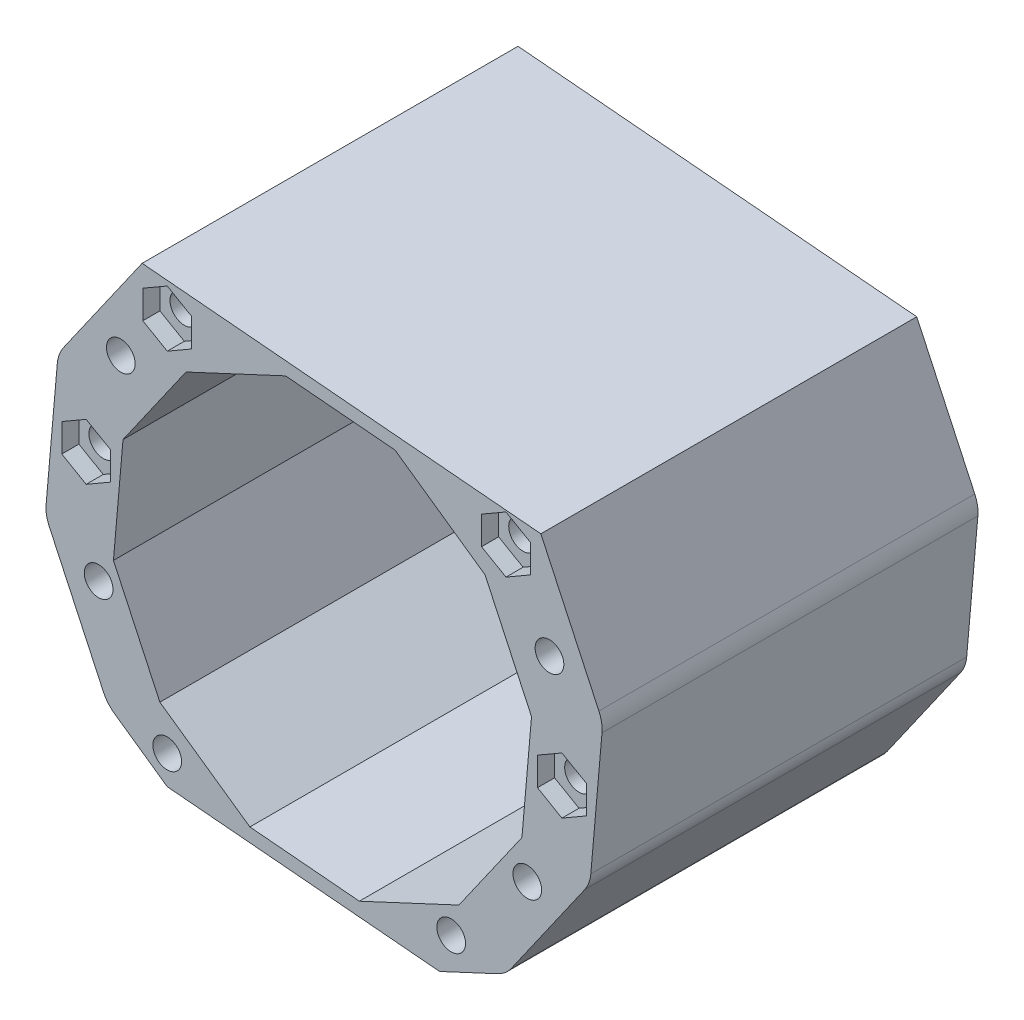
SolidWorks part; units mm, degrees
material "PE faible/moyenne densité"
ref_plane "Plan de face" through (0, 0, 0) normal (0, 0, 1) x (1, 0, 0)
ref_plane "Plan de dessus" through (0, 0, 0) normal (0, 1, 0) x (1, 0, 0)
ref_plane "Plan de droite" through (0, 0, 0) normal (1, 0, 0) x (0, 0, -1)
sketch "Esquisse1" plane through (0, 0, 0) normal (0, 0, 1) x (1, 0, 0)
  line L0 (16.9047, -36.2523) -> (26.6185, -31.7227)
  line L2 (-26.6185, 31.7227) -> (-38.9137, 14.1634)
  line L3 (-38.9137, 14.1634) -> (-40.7819, -7.191)
  line L4 (-40.7819, -7.191) -> (-31.7227, -26.6185)
  line L5 (-31.7227, -26.6185) -> (-22.9431, -32.7661)
  line L7 (26.6185, -31.7227) -> (38.9137, -14.1634)
  line L8 (38.9137, -14.1634) -> (40.7819, 7.191)
  line L9 (40.7819, 7.191) -> (31.7227, 26.6185)
  line L12 (-26.6185, 31.7227) -> (31.7227, 26.6185)
  line L13 (16.9047, -36.2523) -> (-22.9431, -32.7661)
  line L15 (-7.191, 40.7819) -> (-26.6185, 31.7227) [skipped]
  line L16 (14.1634, 38.9137) -> (-7.191, 40.7819) [skipped]
  line L17 (31.7227, 26.6185) -> (14.1634, 38.9137) [skipped]
  line L18 (-14.1634, -38.9137) -> (7.191, -40.7819) [skipped]
  arc A0 (-26.6185, 31.7227) -> (-31.7227, -26.6185) centre (0, 0) ccw construction
  arc A1 (26.6185, -31.7227) -> (31.7227, 26.6185) centre (0, 0) ccw construction
  dimension "D1" = 80
extrude "Boss.-Extru.1" add sketch "Esquisse1" along normal blind 10
sketch "Esquisse2" plane through (0, 0, 10) normal (0, 0, 1) x (1, 0, 0)
  line L0 (38.9137, -14.1634) -> (40.7819, 7.191) construction
  line L1 (-20.1941, 21.1611) -> (-29.4154, 7.9916)
  line L2 (-29.4154, 7.9916) -> (-30.8166, -8.0242)
  line L3 (-30.8166, -8.0242) -> (-24.0222, -22.5948)
  line L4 (-24.0222, -22.5948) -> (-10.8527, -31.8162)
  line L5 (-10.8527, -31.8162) -> (5.163, -33.2174)
  line L6 (5.163, -33.2174) -> (19.7337, -26.423)
  line L7 (19.7337, -26.423) -> (28.9551, -13.2535)
  line L8 (28.9551, -13.2535) -> (30.3563, 2.7622)
  line L9 (30.3563, 2.7622) -> (23.5618, 17.3329)
  line L10 (23.5618, 17.3329) -> (10.3924, 26.5543)
  line L11 (10.3924, 26.5543) -> (-5.6234, 27.9555)
  line L12 (-5.6234, 27.9555) -> (-20.1941, 21.1611)
  line L13 (-22.9431, -32.7661) -> (16.9047, -36.2523) construction
  line L14 (31.7227, 26.6185) -> (-26.6185, 31.7227)
  line L15 (-26.6185, 31.7227) -> (-38.9137, 14.1634)
  line L16 (-38.9137, 14.1634) -> (-40.7819, -7.191)
  line L17 (-40.7819, -7.191) -> (-31.7227, -26.6185)
  line L18 (-31.7227, -26.6185) -> (-22.9431, -32.7661)
  line L19 (-22.9431, -32.7661) -> (16.9047, -36.2523)
  line L20 (16.9047, -36.2523) -> (26.6185, -31.7227)
  line L21 (26.6185, -31.7227) -> (38.9137, -14.1634)
  line L22 (38.9137, -14.1634) -> (40.7819, 7.191)
  line L23 (40.7819, 7.191) -> (31.7227, 26.6185)
  circle A0 centre (-0.2302, -2.631) radius 30 construction
  circle A1 centre (34.8067, -3.7381) radius 2.1
  circle A2 centre (29.7378, -18.4699) radius 2.1
  circle A7 centre (-32.9816, -11.7341) radius 2.1
  circle A8 centre (-34.8067, 3.7381) radius 2.1
  circle A9 centre (-29.7378, 18.4699) radius 2.1
  circle A14 centre (32.9816, 11.7341) radius 2.1
  arc A15 (4.8041, -32.787) -> (2.9306, -33.0221) centre (4.1008, -34.7658) ccw [skipped]
  circle A16 centre (18.6013, -30.822) radius 2.1
  arc A17 (-13.4301, -33.5984) -> (-9.4662, -33.9452) centre (-11.3896, -33.1022) ccw [skipped]
  circle A18 centre (-24.6241, -24.8823) radius 2.1 [skipped]
  circle A19 centre (18.779, -29.5436) radius 2.1 [skipped]
  circle A20 centre (11.3896, 33.1022) radius 2.1 [skipped]
  circle A21 centre (-4.1008, 34.7658) radius 2.1 [skipped]
  circle A22 centre (24.6241, 24.8823) radius 2.1 [skipped]
  arc A23 (-17.1728, 30.8963) -> (-20.126, 31.1547) centre (-18.779, 29.5436) ccw [skipped]
  circle A24 centre (-22.9431, -28.5378) radius 2.1
  circle A25 centre (26.6185, 22.7059) radius 2.1
  circle A26 centre (-22.9431, 26.5543) radius 2.1
  point P68 (0, 0)
  dimension "D3" = 4.2
  dimension "D6" = 4.2
  dimension "D7" = 4.2
  dimension "D8" = 4.2
  dimension "D9" = 4.2
  dimension "D1" = 60
  dimension "D2" = 2
  dimension "D4" = 5
  dimension "D5" = 14
extrude "Boss.-Extru.2" add sketch "Esquisse2" along normal blind 45
sketch "Esquisse3" plane through (0, 0, 55) normal (0, 0, 1) x (1, 0, 0)
  line L1 (-34.8067, -0.3784) -> (-31.2417, 1.6798)
  line L2 (-31.2417, 1.6798) -> (-31.2417, 5.7963)
  line L3 (-31.2417, 5.7963) -> (-34.8067, 7.8546)
  line L4 (-34.8067, 7.8546) -> (-38.3717, 5.7963)
  line L5 (-38.3717, 5.7963) -> (-38.3717, 1.6798)
  line L6 (-38.3717, 1.6798) -> (-34.8067, -0.3784)
  line L7 (-22.9431, 22.4262) -> (-19.3681, 24.4902)
  line L8 (-19.3681, 24.4902) -> (-19.3681, 28.6183)
  line L9 (-19.3681, 28.6183) -> (-22.9431, 30.6823)
  line L10 (-22.9431, 30.6823) -> (-26.5181, 28.6183)
  line L11 (-26.5181, 28.6183) -> (-26.5181, 24.4902)
  line L12 (-26.5181, 24.4902) -> (-22.9431, 22.4262)
  line L13 (30.1935, 20.6418) -> (30.1935, 24.7699)
  line L14 (30.1935, 24.7699) -> (26.6185, 26.8339)
  line L15 (26.6185, 26.8339) -> (23.0435, 24.7699)
  line L16 (23.0435, 24.7699) -> (23.0435, 20.6418)
  line L17 (23.0435, 20.6418) -> (26.6185, 18.5778)
  line L18 (26.6185, 18.5778) -> (30.1935, 20.6418)
  line L19 (38.3817, -5.8021) -> (38.3817, -1.6741)
  line L20 (38.3817, -1.6741) -> (34.8067, 0.39)
  line L21 (34.8067, 0.39) -> (31.2317, -1.6741)
  line L22 (31.2317, -1.6741) -> (31.2317, -5.8021)
  line L23 (31.2317, -5.8021) -> (34.8067, -7.8661)
  line L24 (34.8067, -7.8661) -> (38.3817, -5.8021)
  circle A0 centre (-34.8067, 3.7381) radius 3.565 construction
  circle A1 centre (-22.9431, 26.5543) radius 3.575 construction
  circle A2 centre (26.6185, 22.7059) radius 3.575 construction
  circle A3 centre (34.8067, -3.7381) radius 3.575 construction
extrude "Enlèv. mat.-Extru.1" cut sketch "Esquisse3" against normal blind 2.5
fillet "Congé1" radius 5 6 edges at (-31.7227, -26.6185, 27.5) (-40.7819, -7.191, 27.5) (-38.9137, 14.1634, 27.5) (40.7819, 7.191, 27.5) (38.9137, -14.1634, 27.5) (26.6185, -31.7227, 27.5)
